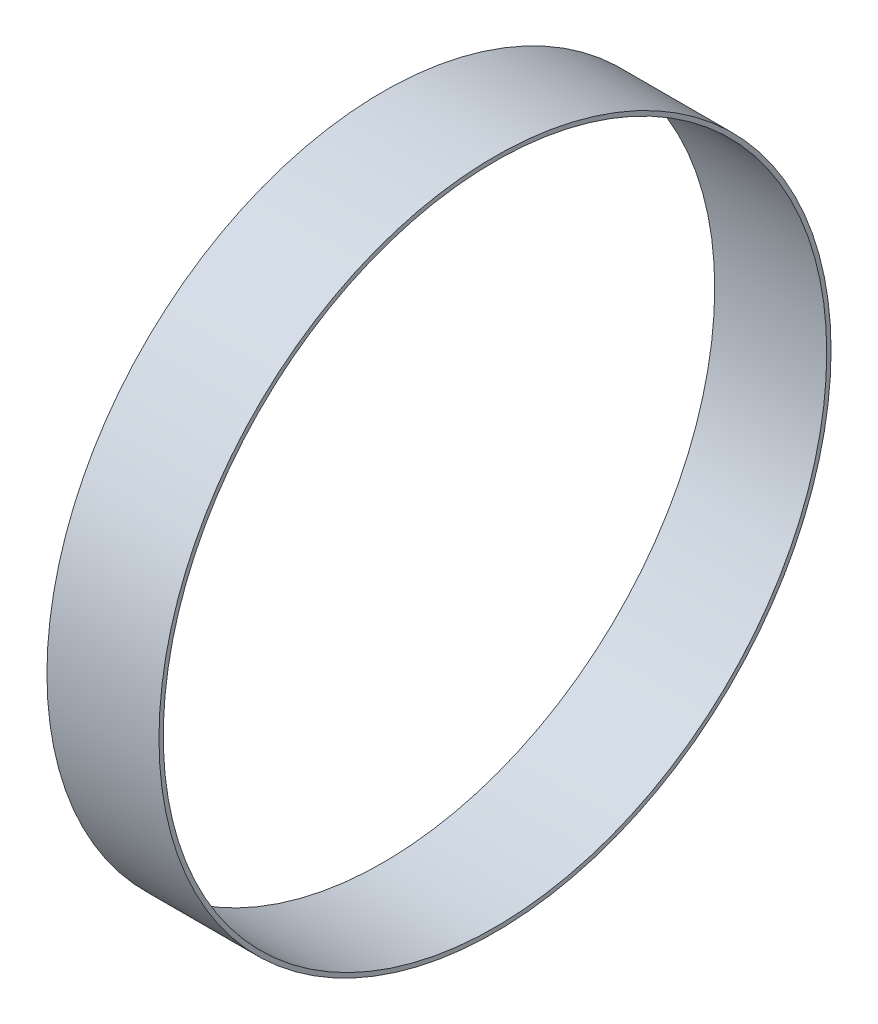
SolidWorks part; units mm, degrees
ref_plane "Front Plane" through (0, 0, 0) normal (0, 0, 1) x (1, 0, 0)
ref_plane "Top Plane" through (0, 0, 0) normal (0, 1, 0) x (1, 0, 0)
ref_plane "Right Plane" through (0, 0, 0) normal (1, 0, 0) x (0, 0, -1)
sketch "Sketch2" plane through (0, 0, 0) normal (1, 0, 0) x (0, 0, -1)
  circle A0 centre (0, 0) radius 76.2
  dimension "D1" = 152.4
extrude "Boss-Extrude1" add sketch "Sketch2" along normal blind 25.4
sketch "Sketch3" plane through (25.4, 0, 0) normal (1, 0, 0) x (0, 0, -1)
  circle A0 centre (0, 0) radius 75.2221
  dimension "D1" = 150.4442
extrude "Cut-Extrude1" cut sketch "Sketch3" against normal through all
